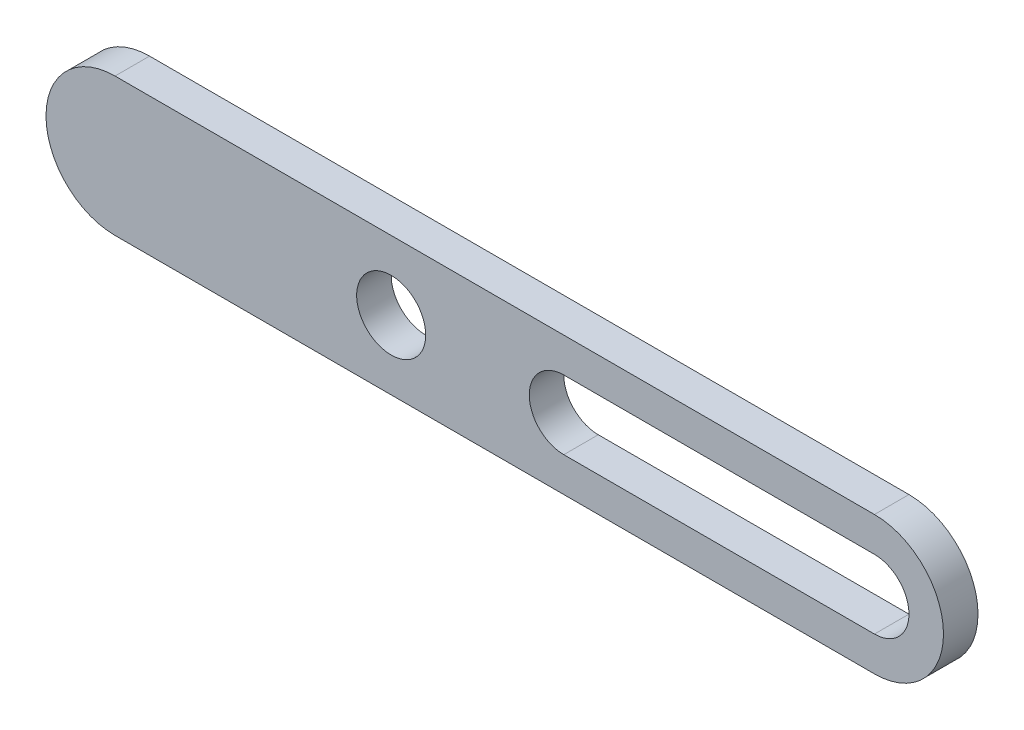
SolidWorks part; units mm, degrees
ref_plane "Front Plane" through (0, 0, 0) normal (0, 0, 1) x (1, 0, 0)
ref_plane "Top Plane" through (0, 0, 0) normal (0, 1, 0) x (1, 0, 0)
ref_plane "Right Plane" through (0, 0, 0) normal (1, 0, 0) x (0, 0, -1)
sketch "Sketch1" plane through (0, 0, 0) normal (0, 0, 1) x (1, 0, 0)
  line L0 (-88.9, 0) -> (88.9, 0) construction
  line L1 (88.9, 12.7) -> (-25.4, 12.7)
  line L3 (-88.9, 25.4) -> (-88.9, -25.4) construction
  line L4 (-88.9, 25.4) -> (88.9, 25.4) construction
  line L7 (-88.9, -25.4) -> (88.9, -25.4) construction
  line L8 (-88.9, 25.4) -> (88.9, 25.4)
  line L9 (-88.9, -25.4) -> (88.9, -25.4)
  line L10 (-88.9, 25.4) -> (-190.5, 25.4)
  line L11 (-88.9, -25.4) -> (-190.5, -25.4)
  line L12 (-25.4, -12.7) -> (88.9, -12.7)
  circle A0 centre (-88.9, 0) radius 12.7
  arc A1 (88.9, -12.7) -> (88.9, 12.7) centre (88.9, 0) ccw
  arc A9 (88.9, 25.4) -> (88.9, -25.4) centre (88.9, 0) cw
  arc A12 (-25.4, 12.7) -> (-25.4, -12.7) centre (-25.4, 0) ccw
  arc A13 (-190.5, 25.4) -> (-190.5, -25.4) centre (-190.5, 0) ccw
  arc A14 (25.4, 0) -> (12.7, 12.7) centre (12.7, 0) ccw [skipped]
  arc A15 (63.5, 0) -> (50.8, 12.7) centre (50.8, 0) ccw [skipped]
  point P3 (0, 0)
  point P14 (-88.9, 0)
  dimension "D2" = 25.4
  dimension "D3" = 25.4
  dimension "D6" = 4
  dimension "D5" = 177.8
  dimension "D1" = 177.8
  dimension "D4" = 50.8
  dimension "D8" = 101.6
extrude "Boss-Extrude1" add sketch "Sketch1" along normal blind 12.7
equation "\"CrankWidth\"=0.5"
equation "\"D1@Boss-Extrude1\"=\"CrankWidth\""
